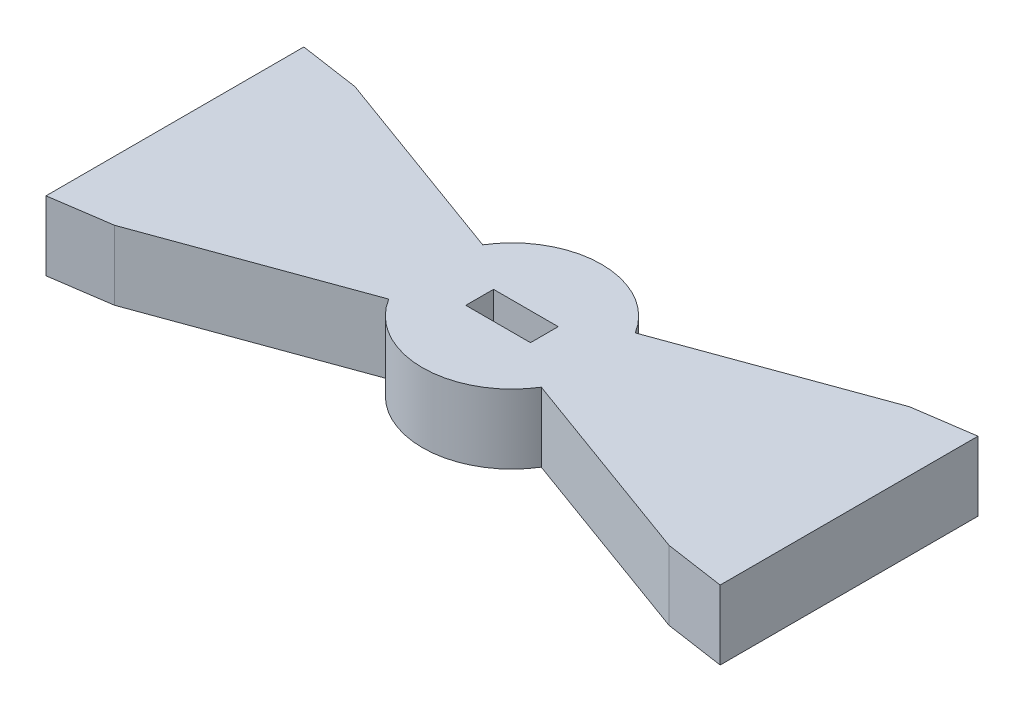
SolidWorks part; units mm, degrees
ref_plane "Front Plane" through (0, 0, 0) normal (0, 0, 1) x (1, 0, 0)
ref_plane "Top Plane" through (0, 0, 0) normal (0, 1, 0) x (1, 0, 0)
ref_plane "Right Plane" through (0, 0, 0) normal (1, 0, 0) x (0, 0, -1)
sketch "Sketch1" plane through (0, 0, 0) normal (0, 1, 0) x (1, 0, 0)
  line L0 (9.2654, 3.5437) -> (9.2654, -3.5437)
  line L2 (7.62, 3.302) -> (2.0965, 1.2916) construction
  line L3 (2.0965, 1.2916) -> (7.62, 3.302)
  line L4 (7.62, 3.302) -> (9.2654, 3.5437)
  line L6 (0, 0) -> (0, -12.1575) construction
  line L7 (-7.62, -3.302) -> (-9.2654, -3.5437)
  line L8 (2.0965, -1.2916) -> (7.62, -3.302)
  line L9 (7.62, -3.302) -> (9.2654, -3.5437)
  line L11 (-2.0965, 1.2916) -> (-7.62, 3.302)
  line L16 (-2.0965, -1.2916) -> (-7.62, -3.302)
  line L17 (-9.2654, 3.5437) -> (-9.2654, -3.5437)
  line L18 (-7.62, 3.302) -> (-9.2654, 3.5437)
  arc A1 (-2.0965, 1.2916) -> (2.0965, 1.2916) centre (0, 0) cw
  arc A2 (-2.0965, -1.2916) -> (2.0965, -1.2916) centre (0, 0) ccw
  point P3 (8.4427, -3.4228)
  point P8 (-8.4427, -3.4228)
extrude "Boss-Extrude3" add sketch "Sketch1" along normal blind 1.905
sketch "Sketch2" plane through (0, 1.905, 0) normal (0, 1, 0) x (1, 0, 0)
  line L1 (-0.889, -0.381) -> (0.889, -0.381)
  line L2 (-0.889, -0.381) -> (-0.889, 0.381)
  line L3 (-0.889, 0.381) -> (0.889, 0.381)
  line L4 (0.889, -0.381) -> (0.889, 0.381)
  line L5 (-0.889, -0.381) -> (0.889, 0.381) construction
  line L6 (-0.889, 0.381) -> (0.889, -0.381) construction
  point P0 (0, 0)
  dimension "D1" = 1.778
  dimension "D2" = 0.762
extrude "Cut-Extrude1" cut sketch "Sketch2" against normal blind 2.54
